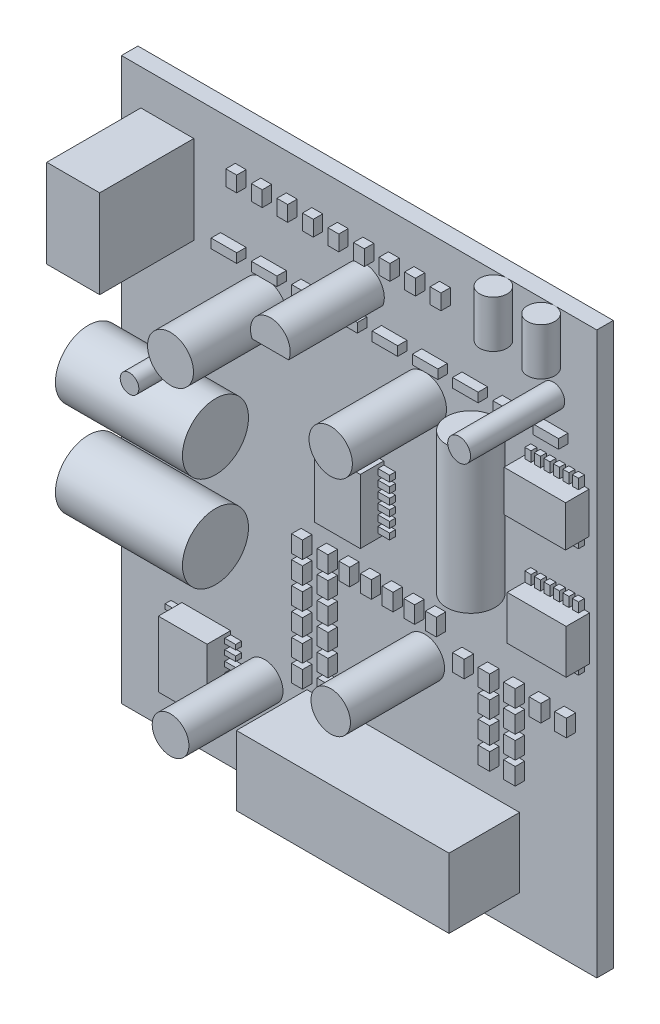
SolidWorks part; units mm, degrees
ref_plane "Plan de face" through (0, 0, 0) normal (0, 0, 1) x (1, 0, 0)
ref_plane "Plan de dessus" through (0, 0, 0) normal (0, 1, 0) x (1, 0, 0)
ref_plane "Plan de droite" through (0, 0, 0) normal (1, 0, 0) x (0, 0, -1)
sketch "Esquisse1" plane through (0, 0, 0) normal (0, 0, 1) x (1, 0, 0)
  line L1 (0, 0) -> (40.4, 0)
  line L2 (0, 0) -> (0, 47.7)
  line L3 (0, 47.7) -> (40.4, 47.7)
  line L4 (40.4, 0) -> (40.4, 47.7)
  dimension "D1" = 40.4
  dimension "D2" = 47.7
extrude "Extrusion1" add sketch "Esquisse1" along normal blind 1.4
sketch "Esquisse2" plane through (0, 0, 1.4) normal (0, 0, 1) x (1, 0, 0)
  line L1 (1.6498, 44.6665) -> (6.1498, 44.6665)
  line L2 (1.6498, 44.6665) -> (1.6498, 37.1665)
  line L3 (1.6498, 37.1665) -> (6.1498, 37.1665)
  line L4 (6.1498, 44.6665) -> (6.1498, 37.1665)
  dimension "D1" = 7.5
  dimension "D2" = 4.5
extrude "Extrusion2" add sketch "Esquisse2" along normal blind 8
sketch "Esquisse3" plane through (0, 0, 1.4) normal (0, 0, 1) x (1, 0, 0)
  line L0 (19.0987, 40.3981) -> (22.2105, 40.3981)
  circle A0 centre (8.6862, 31.9057) radius 0.7919
  circle A1 centre (12.1715, 35.4567) radius 1.9519
  circle A2 centre (25.7839, 35.4567) radius 1.8425
  arc A3 (22.2105, 40.3981) -> (19.0987, 40.3981) centre (20.6546, 41.0464) ccw
  circle A4 centre (12.1715, 7.7708) radius 1.559
  circle A5 centre (25.7839, 16.3204) radius 1.6766
  circle A6 centre (36.7002, 41.0464) radius 0.9709
extrude "Extrusion3" add sketch "Esquisse3" along normal blind 8
sketch "Esquisse4" plane through (0, 0, 1.4) normal (0, 0, 1) x (1, 0, 0)
  line L1 (15.7714, 8.9071) -> (33.8392, 8.9071)
  line L2 (15.7714, 8.9071) -> (15.7714, 2.9981)
  line L3 (15.7714, 2.9981) -> (33.8392, 2.9981)
  line L4 (33.8392, 8.9071) -> (33.8392, 2.9981)
extrude "Extrusion4" add sketch "Esquisse4" along normal blind 6
ref_plane "Plan1" through (0, 25, 0) normal (0, 1, 0) x (-1, 0, 0)
sketch "Esquisse5" plane through (0, 25, 0) normal (0, 1, 0) x (-1, 0, 0)
  line L0 (-40.4, 1.4) -> (0, 1.4) construction
  circle A0 centre (-31.7474, 3.4583) radius 2.0583
extrude "Extrusion5" add sketch "Esquisse5" along normal blind 12
sketch "Esquisse6" plane through (0, 0, 1.4) normal (0, 0, 1) x (1, 0, 0)
  line L1 (34.5087, 35.654) -> (39.7463, 35.654)
  line L2 (34.5087, 35.654) -> (34.5087, 32.1687)
  line L3 (34.5087, 32.1687) -> (39.7463, 32.1687)
  line L4 (39.7463, 35.654) -> (39.7463, 32.1687)
  line L5 (34.7835, 26.5791) -> (39.7973, 26.5791)
  line L6 (34.7835, 26.5791) -> (34.7835, 22.8307)
  line L7 (34.7835, 22.8307) -> (39.7973, 22.8307)
  line L8 (39.7973, 26.5791) -> (39.7973, 22.8307)
  line L9 (18.4188, 29.0122) -> (22.2986, 29.0122)
  line L10 (18.4188, 29.0122) -> (18.4188, 23.5541)
  line L11 (18.4188, 23.5541) -> (22.2986, 23.5541)
  line L12 (22.2986, 29.0122) -> (22.2986, 23.5541)
  line L13 (5.1351, 10.0074) -> (9.2781, 10.0074)
  line L14 (5.1351, 10.0074) -> (5.1351, 4.4178)
  line L15 (5.1351, 4.4178) -> (9.2781, 4.4178)
  line L16 (9.2781, 10.0074) -> (9.2781, 4.4178)
extrude "Extrusion6" add sketch "Esquisse6" along normal blind 2
sketch "Esquisse7" plane through (0, 0, 1.4) normal (0, 0, 1) x (1, 0, 0)
  line L1 (34.7835, 35.654) -> (35.3096, 35.654)
  line L2 (34.7835, 35.654) -> (34.7835, 36.5089)
  line L3 (34.7835, 36.5089) -> (35.3096, 36.5089)
  line L4 (35.3096, 35.654) -> (35.3096, 36.5089)
  line L5 (35.5906, 35.654) -> (35.5906, 36.5089)
  line L6 (35.5906, 35.654) -> (36.1167, 35.654)
  line L7 (35.5906, 36.5089) -> (36.1167, 36.5089)
  line L8 (36.1167, 35.654) -> (36.1167, 36.5089)
  line L9 (36.3977, 35.654) -> (36.3977, 36.5089)
  line L10 (36.3977, 35.654) -> (36.9237, 35.654)
  line L11 (36.3977, 36.5089) -> (36.9237, 36.5089)
  line L12 (36.9237, 35.654) -> (36.9237, 36.5089)
  line L13 (37.2047, 35.654) -> (37.2047, 36.5089)
  line L14 (37.2047, 35.654) -> (37.7308, 35.654)
  line L15 (37.2047, 36.5089) -> (37.7308, 36.5089)
  line L16 (37.7308, 35.654) -> (37.7308, 36.5089)
  line L17 (38.0118, 35.654) -> (38.0118, 36.5089)
  line L18 (38.0118, 35.654) -> (38.5379, 35.654)
  line L19 (38.0118, 36.5089) -> (38.5379, 36.5089)
  line L20 (38.5379, 35.654) -> (38.5379, 36.5089)
  line L21 (38.8189, 35.654) -> (38.8189, 36.5089)
  line L22 (38.8189, 35.654) -> (39.345, 35.654)
  line L23 (38.8189, 36.5089) -> (39.345, 36.5089)
  line L24 (39.345, 35.654) -> (39.345, 36.5089)
  line L25 (39.7463, 33.9114) -> (36.0147, 33.9114) construction
  line L26 (39.7463, 32.1687) -> (39.7463, 35.654) construction
  line L27 (39.345, 32.1687) -> (39.345, 31.3138)
  line L28 (38.8189, 31.3138) -> (39.345, 31.3138)
  line L29 (38.8189, 32.1687) -> (39.345, 32.1687)
  line L30 (38.8189, 32.1687) -> (38.8189, 31.3138)
  line L31 (38.5379, 32.1687) -> (38.5379, 31.3138)
  line L32 (38.0118, 31.3138) -> (38.5379, 31.3138)
  line L33 (38.0118, 32.1687) -> (38.5379, 32.1687)
  line L34 (38.0118, 32.1687) -> (38.0118, 31.3138)
  line L35 (37.7308, 32.1687) -> (37.7308, 31.3138)
  line L36 (37.2047, 31.3138) -> (37.7308, 31.3138)
  line L37 (37.2047, 32.1687) -> (37.7308, 32.1687)
  line L38 (37.2047, 32.1687) -> (37.2047, 31.3138)
  line L39 (36.9237, 32.1687) -> (36.9237, 31.3138)
  line L40 (36.3977, 31.3138) -> (36.9237, 31.3138)
  line L41 (36.3977, 32.1687) -> (36.9237, 32.1687)
  line L42 (36.3977, 32.1687) -> (36.3977, 31.3138)
  line L43 (36.1167, 32.1687) -> (36.1167, 31.3138)
  line L44 (35.5906, 31.3138) -> (36.1167, 31.3138)
  line L45 (35.5906, 32.1687) -> (36.1167, 32.1687)
  line L46 (35.5906, 32.1687) -> (35.5906, 31.3138)
  line L47 (35.3096, 32.1687) -> (35.3096, 31.3138)
  line L48 (34.7835, 31.3138) -> (35.3096, 31.3138)
  line L49 (34.7835, 32.1687) -> (34.7835, 31.3138)
  line L50 (34.7835, 32.1687) -> (35.3096, 32.1687)
  line L52 (34.7835, 26.5791) -> (35.3096, 26.5791)
  line L53 (34.7835, 26.5791) -> (34.7835, 27.4044)
  line L54 (34.7835, 27.4044) -> (35.3096, 27.4044)
  line L55 (35.3096, 26.5791) -> (35.3096, 27.4044)
  line L56 (35.5906, 26.5791) -> (35.5906, 27.4044)
  line L57 (35.5906, 27.4044) -> (36.1167, 27.4044)
  line L58 (36.1167, 26.5791) -> (36.1167, 27.4044)
  line L59 (35.5906, 26.5791) -> (36.1167, 26.5791)
  line L60 (36.3977, 26.5791) -> (36.3977, 27.4044)
  line L61 (36.3977, 27.4044) -> (36.9237, 27.4044)
  line L62 (36.9237, 26.5791) -> (36.9237, 27.4044)
  line L63 (36.3977, 26.5791) -> (36.9237, 26.5791)
  line L64 (37.2047, 26.5791) -> (37.2047, 27.4044)
  line L65 (37.2047, 27.4044) -> (37.7308, 27.4044)
  line L66 (37.7308, 26.5791) -> (37.7308, 27.4044)
  line L67 (37.2047, 26.5791) -> (37.7308, 26.5791)
  line L68 (38.0118, 26.5791) -> (38.0118, 27.4044)
  line L69 (38.0118, 27.4044) -> (38.5379, 27.4044)
  line L70 (38.5379, 26.5791) -> (38.5379, 27.4044)
  line L71 (38.0118, 26.5791) -> (38.5379, 26.5791)
  line L72 (38.8189, 26.5791) -> (38.8189, 27.4044)
  line L73 (38.8189, 27.4044) -> (39.345, 27.4044)
  line L74 (39.345, 26.5791) -> (39.345, 27.4044)
  line L75 (38.8189, 26.5791) -> (39.345, 26.5791)
  line L76 (39.7973, 24.7049) -> (35.7927, 24.7049) construction
  line L77 (39.7973, 22.8307) -> (39.7973, 26.5791) construction
  line L78 (38.8189, 22.8307) -> (39.345, 22.8307)
  line L79 (39.345, 22.8307) -> (39.345, 22.0054)
  line L80 (38.8189, 22.0054) -> (39.345, 22.0054)
  line L81 (38.8189, 22.8307) -> (38.8189, 22.0054)
  line L82 (38.0118, 22.8307) -> (38.5379, 22.8307)
  line L83 (38.5379, 22.8307) -> (38.5379, 22.0054)
  line L84 (38.0118, 22.0054) -> (38.5379, 22.0054)
  line L85 (38.0118, 22.8307) -> (38.0118, 22.0054)
  line L86 (37.2047, 22.8307) -> (37.7308, 22.8307)
  line L87 (37.7308, 22.8307) -> (37.7308, 22.0054)
  line L88 (37.2047, 22.0054) -> (37.7308, 22.0054)
  line L89 (37.2047, 22.8307) -> (37.2047, 22.0054)
  line L90 (36.3977, 22.8307) -> (36.9237, 22.8307)
  line L91 (36.9237, 22.8307) -> (36.9237, 22.0054)
  line L92 (36.3977, 22.0054) -> (36.9237, 22.0054)
  line L93 (36.3977, 22.8307) -> (36.3977, 22.0054)
  line L94 (35.5906, 22.8307) -> (36.1167, 22.8307)
  line L95 (36.1167, 22.8307) -> (36.1167, 22.0054)
  line L96 (35.5906, 22.0054) -> (36.1167, 22.0054)
  line L97 (35.5906, 22.8307) -> (35.5906, 22.0054)
  line L98 (35.3096, 22.8307) -> (35.3096, 22.0054)
  line L99 (34.7835, 22.0054) -> (35.3096, 22.0054)
  line L100 (34.7835, 22.8307) -> (34.7835, 22.0054)
  line L101 (34.7835, 22.8307) -> (35.3096, 22.8307)
  line L102 (22.2986, 23.5541) -> (22.2986, 29.0122) construction
  line L103 (22.2986, 28.6995) -> (23.2857, 28.6995)
  line L104 (22.2986, 28.6995) -> (22.2986, 28.1814)
  line L105 (22.2986, 28.1814) -> (23.2857, 28.1814)
  line L106 (23.2857, 28.6995) -> (23.2857, 28.1814)
  line L107 (22.2986, 27.3304) -> (23.2857, 27.3304)
  line L108 (22.2986, 27.8484) -> (22.2986, 27.3304)
  line L109 (22.2986, 27.8484) -> (23.2857, 27.8484)
  line L110 (23.2857, 27.8484) -> (23.2857, 27.3304)
  line L111 (22.2986, 26.4793) -> (23.2857, 26.4793)
  line L112 (22.2986, 26.9974) -> (22.2986, 26.4793)
  line L113 (22.2986, 26.9974) -> (23.2857, 26.9974)
  line L114 (23.2857, 26.9974) -> (23.2857, 26.4793)
  line L115 (22.2986, 25.6282) -> (23.2857, 25.6282)
  line L116 (22.2986, 26.1463) -> (22.2986, 25.6282)
  line L117 (22.2986, 26.1463) -> (23.2857, 26.1463)
  line L118 (23.2857, 26.1463) -> (23.2857, 25.6282)
  line L119 (22.2986, 24.7772) -> (23.2857, 24.7772)
  line L120 (22.2986, 25.2952) -> (22.2986, 24.7772)
  line L121 (22.2986, 25.2952) -> (23.2857, 25.2952)
  line L122 (23.2857, 25.2952) -> (23.2857, 24.7772)
  line L123 (22.2986, 23.9261) -> (23.2857, 23.9261)
  line L124 (22.2986, 24.4441) -> (22.2986, 23.9261)
  line L125 (22.2986, 24.4441) -> (23.2857, 24.4441)
  line L126 (23.2857, 24.4441) -> (23.2857, 23.9261)
  line L127 (20.3587, 29.0122) -> (20.3587, 22.2707) construction
  line L128 (22.2986, 29.0122) -> (18.4188, 29.0122) construction
  line L129 (17.4318, 24.4441) -> (17.4318, 23.9261)
  line L130 (18.4188, 24.4441) -> (17.4318, 24.4441)
  line L131 (18.4188, 24.4441) -> (18.4188, 23.9261)
  line L132 (18.4188, 23.9261) -> (17.4318, 23.9261)
  line L133 (17.4318, 25.2952) -> (17.4318, 24.7772)
  line L134 (18.4188, 25.2952) -> (17.4318, 25.2952)
  line L135 (18.4188, 25.2952) -> (18.4188, 24.7772)
  line L136 (18.4188, 24.7772) -> (17.4318, 24.7772)
  line L137 (17.4318, 26.1463) -> (17.4318, 25.6282)
  line L138 (18.4188, 26.1463) -> (17.4318, 26.1463)
  line L139 (18.4188, 26.1463) -> (18.4188, 25.6282)
  line L140 (18.4188, 25.6282) -> (17.4318, 25.6282)
  line L141 (17.4318, 26.9974) -> (17.4318, 26.4793)
  line L142 (18.4188, 26.9974) -> (17.4318, 26.9974)
  line L143 (18.4188, 26.9974) -> (18.4188, 26.4793)
  line L144 (18.4188, 26.4793) -> (17.4318, 26.4793)
  line L145 (17.4318, 27.8484) -> (17.4318, 27.3304)
  line L146 (18.4188, 27.8484) -> (17.4318, 27.8484)
  line L147 (18.4188, 27.8484) -> (18.4188, 27.3304)
  line L148 (18.4188, 27.3304) -> (17.4318, 27.3304)
  line L149 (17.4318, 28.6995) -> (17.4318, 28.1814)
  line L150 (18.4188, 28.1814) -> (17.4318, 28.1814)
  line L151 (18.4188, 28.6995) -> (18.4188, 28.1814)
  line L152 (18.4188, 28.6995) -> (17.4318, 28.6995)
  line L153 (9.2781, 4.4178) -> (9.2781, 10.0074) construction
  line L154 (9.2781, 9.7011) -> (10.2039, 9.7011)
  line L155 (9.2781, 9.7011) -> (9.2781, 9.2913)
  line L156 (9.2781, 9.2913) -> (10.2039, 9.2913)
  line L157 (10.2039, 9.7011) -> (10.2039, 9.2913)
  line L158 (9.2781, 8.8523) -> (10.2039, 8.8523)
  line L159 (9.2781, 8.8523) -> (9.2781, 8.4425)
  line L160 (9.2781, 8.4425) -> (10.2039, 8.4425)
  line L161 (10.2039, 8.8523) -> (10.2039, 8.4425)
  line L162 (9.2781, 8.0034) -> (10.2039, 8.0034)
  line L163 (9.2781, 8.0034) -> (9.2781, 7.5936)
  line L164 (9.2781, 7.5936) -> (10.2039, 7.5936)
  line L165 (10.2039, 8.0034) -> (10.2039, 7.5936)
  line L166 (9.2781, 7.1546) -> (10.2039, 7.1546)
  line L167 (9.2781, 7.1546) -> (9.2781, 6.7448)
  line L168 (9.2781, 6.7448) -> (10.2039, 6.7448)
  line L169 (10.2039, 7.1546) -> (10.2039, 6.7448)
  line L170 (9.2781, 6.3057) -> (10.2039, 6.3057)
  line L171 (9.2781, 6.3057) -> (9.2781, 5.896)
  line L172 (9.2781, 5.896) -> (10.2039, 5.896)
  line L173 (10.2039, 6.3057) -> (10.2039, 5.896)
  line L174 (9.2781, 5.4569) -> (10.2039, 5.4569)
  line L175 (9.2781, 5.4569) -> (9.2781, 5.0471)
  line L176 (9.2781, 5.0471) -> (10.2039, 5.0471)
  line L177 (10.2039, 5.4569) -> (10.2039, 5.0471)
  line L178 (7.2066, 10.0074) -> (7.2066, 2.9982) construction
  line L179 (9.2781, 10.0074) -> (5.1351, 10.0074) construction
  line L180 (4.2093, 5.4569) -> (4.2093, 5.0471)
  line L181 (5.1351, 5.0471) -> (4.2093, 5.0471)
  line L182 (5.1351, 5.4569) -> (5.1351, 5.0471)
  line L183 (5.1351, 5.4569) -> (4.2093, 5.4569)
  line L184 (4.2093, 6.3057) -> (4.2093, 5.896)
  line L185 (5.1351, 5.896) -> (4.2093, 5.896)
  line L186 (5.1351, 6.3057) -> (5.1351, 5.896)
  line L187 (5.1351, 6.3057) -> (4.2093, 6.3057)
  line L188 (4.2093, 7.1546) -> (4.2093, 6.7448)
  line L189 (5.1351, 6.7448) -> (4.2093, 6.7448)
  line L190 (5.1351, 7.1546) -> (5.1351, 6.7448)
  line L191 (5.1351, 7.1546) -> (4.2093, 7.1546)
  line L192 (4.2093, 8.0034) -> (4.2093, 7.5936)
  line L193 (5.1351, 7.5936) -> (4.2093, 7.5936)
  line L194 (5.1351, 8.0034) -> (5.1351, 7.5936)
  line L195 (5.1351, 8.0034) -> (4.2093, 8.0034)
  line L196 (4.2093, 8.8523) -> (4.2093, 8.4425)
  line L197 (5.1351, 8.4425) -> (4.2093, 8.4425)
  line L198 (5.1351, 8.8523) -> (5.1351, 8.4425)
  line L199 (5.1351, 8.8523) -> (4.2093, 8.8523)
  line L200 (4.2093, 9.7011) -> (4.2093, 9.2913)
  line L201 (5.1351, 9.2913) -> (4.2093, 9.2913)
  line L202 (5.1351, 9.7011) -> (5.1351, 9.2913)
  line L203 (5.1351, 9.7011) -> (4.2093, 9.7011)
extrude "Extrusion7" add sketch "Esquisse7" along normal blind 0.5
sketch "Esquisse8" plane through (0, 0, 1.4) normal (0, 0, 1) x (1, 0, 0)
  line L0 (11.8427, 44.5974) -> (12.7634, 44.5974)
  line L1 (9.6726, 44.5974) -> (10.5933, 44.5974)
  line L2 (9.6726, 44.5974) -> (9.6726, 43.2822)
  line L3 (9.6726, 43.2822) -> (10.5933, 43.2822)
  line L4 (10.5933, 44.5974) -> (10.5933, 43.2822)
  line L5 (11.8427, 44.5974) -> (11.8427, 43.2822)
  line L6 (11.8427, 43.2822) -> (12.7634, 43.2822)
  line L7 (12.7634, 44.5974) -> (12.7634, 43.2822)
  line L8 (14.0128, 44.5974) -> (14.9335, 44.5974)
  line L9 (14.0128, 44.5974) -> (14.0128, 43.2822)
  line L10 (14.0128, 43.2822) -> (14.9335, 43.2822)
  line L11 (14.9335, 44.5974) -> (14.9335, 43.2822)
  line L12 (16.1829, 44.5974) -> (17.1036, 44.5974)
  line L13 (16.1829, 44.5974) -> (16.1829, 43.2822)
  line L14 (16.1829, 43.2822) -> (17.1036, 43.2822)
  line L15 (17.1036, 44.5974) -> (17.1036, 43.2822)
  line L16 (18.353, 44.5974) -> (19.2737, 44.5974)
  line L17 (18.353, 44.5974) -> (18.353, 43.2822)
  line L18 (18.353, 43.2822) -> (19.2737, 43.2822)
  line L19 (19.2737, 44.5974) -> (19.2737, 43.2822)
  line L20 (20.5231, 44.5974) -> (21.4438, 44.5974)
  line L21 (20.5231, 44.5974) -> (20.5231, 43.2822)
  line L22 (20.5231, 43.2822) -> (21.4438, 43.2822)
  line L23 (21.4438, 44.5974) -> (21.4438, 43.2822)
  line L24 (22.6932, 44.5974) -> (23.6139, 44.5974)
  line L25 (22.6932, 44.5974) -> (22.6932, 43.2822)
  line L26 (22.6932, 43.2822) -> (23.6139, 43.2822)
  line L27 (23.6139, 44.5974) -> (23.6139, 43.2822)
  line L28 (24.8633, 44.5974) -> (25.7839, 44.5974)
  line L29 (24.8633, 44.5974) -> (24.8633, 43.2822)
  line L30 (24.8633, 43.2822) -> (25.7839, 43.2822)
  line L31 (25.7839, 44.5974) -> (25.7839, 43.2822)
  line L32 (27.0334, 44.5974) -> (27.954, 44.5974)
  line L33 (27.0334, 44.5974) -> (27.0334, 43.2822)
  line L34 (27.0334, 43.2822) -> (27.954, 43.2822)
  line L35 (27.954, 44.5974) -> (27.954, 43.2822)
  line L36 (11.8427, 38.0872) -> (14.0128, 38.0872)
  line L37 (8.4232, 38.8763) -> (10.5933, 38.8763)
  line L38 (8.4232, 38.8763) -> (8.4232, 38.0872)
  line L39 (8.4232, 38.0872) -> (10.5933, 38.0872)
  line L40 (10.5933, 38.8763) -> (10.5933, 38.0872)
  line L41 (11.8427, 38.8763) -> (11.8427, 38.0872)
  line L42 (11.8427, 38.8763) -> (14.0128, 38.8763)
  line L43 (14.0128, 38.8763) -> (14.0128, 38.0872)
  line L44 (15.2623, 38.0872) -> (17.4324, 38.0872)
  line L45 (15.2623, 38.8763) -> (15.2623, 38.0872)
  line L46 (15.2623, 38.8763) -> (17.4324, 38.8763)
  line L47 (17.4324, 38.8763) -> (17.4324, 38.0872)
  line L48 (18.6818, 38.0872) -> (20.8519, 38.0872)
  line L49 (18.6818, 38.8763) -> (18.6818, 38.0872)
  line L50 (18.6818, 38.8763) -> (20.8519, 38.8763)
  line L51 (20.8519, 38.8763) -> (20.8519, 38.0872)
  line L52 (22.1014, 38.0872) -> (24.2715, 38.0872)
  line L53 (22.1014, 38.8763) -> (22.1014, 38.0872)
  line L54 (22.1014, 38.8763) -> (24.2715, 38.8763)
  line L55 (24.2715, 38.8763) -> (24.2715, 38.0872)
  line L56 (25.5209, 38.0872) -> (27.691, 38.0872)
  line L57 (25.5209, 38.8763) -> (25.5209, 38.0872)
  line L58 (25.5209, 38.8763) -> (27.691, 38.8763)
  line L59 (27.691, 38.8763) -> (27.691, 38.0872)
  line L60 (28.9405, 38.0872) -> (31.1106, 38.0872)
  line L61 (28.9405, 38.8763) -> (28.9405, 38.0872)
  line L62 (28.9405, 38.8763) -> (31.1106, 38.8763)
  line L63 (31.1106, 38.8763) -> (31.1106, 38.0872)
  line L64 (32.36, 38.0872) -> (34.5301, 38.0872)
  line L65 (32.36, 38.8763) -> (32.36, 38.0872)
  line L66 (32.36, 38.8763) -> (34.5301, 38.8763)
  line L67 (34.5301, 38.8763) -> (34.5301, 38.0872)
  line L68 (35.7795, 38.0872) -> (37.9496, 38.0872)
  line L69 (35.7795, 38.8763) -> (35.7795, 38.0872)
  line L70 (35.7795, 38.8763) -> (37.9496, 38.8763)
  line L71 (37.9496, 38.8763) -> (37.9496, 38.0872)
  line L72 (17.4324, 18.622) -> (18.353, 18.622)
  line L73 (15.2623, 20.5291) -> (16.1829, 20.5291)
  line L74 (15.2623, 20.5291) -> (15.2623, 19.0824)
  line L75 (15.2623, 19.0824) -> (16.1829, 19.0824)
  line L76 (16.1829, 20.5291) -> (16.1829, 19.0824)
  line L77 (17.4324, 20.5291) -> (18.353, 20.5291)
  line L78 (17.4324, 20.5291) -> (17.4324, 19.0824)
  line L79 (17.4324, 19.0824) -> (18.353, 19.0824)
  line L80 (18.353, 20.5291) -> (18.353, 19.0824)
  line L81 (15.2623, 18.622) -> (16.1829, 18.622)
  line L82 (17.4324, 17.1753) -> (18.353, 17.1753)
  line L83 (15.2623, 18.622) -> (15.2623, 17.1753)
  line L84 (17.4324, 18.622) -> (17.4324, 17.1753)
  line L85 (15.2623, 17.1753) -> (16.1829, 17.1753)
  line L86 (16.1829, 18.622) -> (16.1829, 17.1753)
  line L87 (18.353, 18.622) -> (18.353, 17.1753)
  line L88 (17.4324, 16.715) -> (18.353, 16.715)
  line L89 (15.2623, 16.715) -> (16.1829, 16.715)
  line L90 (17.4324, 15.2683) -> (18.353, 15.2683)
  line L91 (15.2623, 16.715) -> (15.2623, 15.2683)
  line L92 (17.4324, 16.715) -> (17.4324, 15.2683)
  line L93 (15.2623, 15.2683) -> (16.1829, 15.2683)
  line L94 (16.1829, 16.715) -> (16.1829, 15.2683)
  line L95 (18.353, 16.715) -> (18.353, 15.2683)
  line L96 (17.4324, 14.8079) -> (18.353, 14.8079)
  line L97 (15.2623, 14.8079) -> (16.1829, 14.8079)
  line L98 (17.4324, 13.3612) -> (18.353, 13.3612)
  line L99 (15.2623, 14.8079) -> (15.2623, 13.3612)
  line L100 (17.4324, 14.8079) -> (17.4324, 13.3612)
  line L101 (15.2623, 13.3612) -> (16.1829, 13.3612)
  line L102 (16.1829, 14.8079) -> (16.1829, 13.3612)
  line L103 (18.353, 14.8079) -> (18.353, 13.3612)
  line L104 (17.4324, 12.9009) -> (18.353, 12.9009)
  line L105 (15.2623, 12.9009) -> (16.1829, 12.9009)
  line L106 (17.4324, 11.4541) -> (18.353, 11.4541)
  line L107 (15.2623, 12.9009) -> (15.2623, 11.4541)
  line L108 (17.4324, 12.9009) -> (17.4324, 11.4541)
  line L109 (15.2623, 11.4541) -> (16.1829, 11.4541)
  line L110 (16.1829, 12.9009) -> (16.1829, 11.4541)
  line L111 (18.353, 12.9009) -> (18.353, 11.4541)
  line L112 (17.4324, 10.9938) -> (18.353, 10.9938)
  line L113 (15.2623, 10.9938) -> (16.1829, 10.9938)
  line L114 (17.4324, 9.5471) -> (18.353, 9.5471)
  line L115 (15.2623, 10.9938) -> (15.2623, 9.5471)
  line L116 (17.4324, 10.9938) -> (17.4324, 9.5471)
  line L117 (15.2623, 9.5471) -> (16.1829, 9.5471)
  line L118 (16.1829, 10.9938) -> (16.1829, 9.5471)
  line L119 (18.353, 10.9938) -> (18.353, 9.5471)
  line L120 (19.2737, 20.5291) -> (20.1943, 20.5291)
  line L121 (20.1943, 20.5291) -> (20.1943, 19.0824)
  line L122 (19.2737, 19.0824) -> (20.1943, 19.0824)
  line L123 (19.2737, 20.5291) -> (19.2737, 19.0824)
  line L124 (21.115, 20.5291) -> (22.0356, 20.5291)
  line L125 (22.0356, 20.5291) -> (22.0356, 19.0824)
  line L126 (21.115, 19.0824) -> (22.0356, 19.0824)
  line L127 (21.115, 20.5291) -> (21.115, 19.0824)
  line L128 (22.9562, 20.5291) -> (23.8769, 20.5291)
  line L129 (23.8769, 20.5291) -> (23.8769, 19.0824)
  line L130 (22.9562, 19.0824) -> (23.8769, 19.0824)
  line L131 (22.9562, 20.5291) -> (22.9562, 19.0824)
  line L132 (24.7975, 20.5291) -> (25.7182, 20.5291)
  line L133 (25.7182, 20.5291) -> (25.7182, 19.0824)
  line L134 (24.7975, 19.0824) -> (25.7182, 19.0824)
  line L135 (24.7975, 20.5291) -> (24.7975, 19.0824)
  line L136 (26.6388, 20.5291) -> (27.5595, 20.5291)
  line L137 (27.5595, 20.5291) -> (27.5595, 19.0824)
  line L138 (26.6388, 19.0824) -> (27.5595, 19.0824)
  line L139 (26.6388, 20.5291) -> (26.6388, 19.0824)
  line L140 (31.1106, 17.1753) -> (32.097, 17.1753)
  line L141 (28.9405, 17.1753) -> (29.9269, 17.1753)
  line L142 (28.9405, 17.1753) -> (28.9405, 18.622)
  line L143 (28.9405, 18.622) -> (29.9269, 18.622)
  line L144 (29.9269, 17.1753) -> (29.9269, 18.622)
  line L145 (32.097, 17.1753) -> (32.097, 18.622)
  line L146 (31.1106, 18.622) -> (32.097, 18.622)
  line L147 (31.1106, 17.1753) -> (31.1106, 18.622)
  line L148 (33.2806, 17.1753) -> (34.2671, 17.1753)
  line L149 (34.2671, 17.1753) -> (34.2671, 18.622)
  line L150 (33.2806, 18.622) -> (34.2671, 18.622)
  line L151 (33.2806, 17.1753) -> (33.2806, 18.622)
  line L152 (35.4507, 17.1753) -> (36.4372, 17.1753)
  line L153 (36.4372, 17.1753) -> (36.4372, 18.622)
  line L154 (35.4507, 18.622) -> (36.4372, 18.622)
  line L155 (35.4507, 17.1753) -> (35.4507, 18.622)
  line L156 (37.6208, 17.1753) -> (38.6073, 17.1753)
  line L157 (38.6073, 17.1753) -> (38.6073, 18.622)
  line L158 (37.6208, 18.622) -> (38.6073, 18.622)
  line L159 (37.6208, 17.1753) -> (37.6208, 18.622)
  line L164 (31.1106, 16.715) -> (32.097, 16.715)
  line L165 (32.097, 15.2683) -> (32.097, 16.715)
  line L166 (31.1106, 15.2683) -> (32.097, 15.2683)
  line L167 (31.1106, 15.2683) -> (31.1106, 16.715)
  line L168 (31.1106, 14.8079) -> (32.097, 14.8079)
  line L169 (32.097, 13.3612) -> (32.097, 14.8079)
  line L170 (31.1106, 13.3612) -> (32.097, 13.3612)
  line L171 (31.1106, 13.3612) -> (31.1106, 14.8079)
  line L172 (31.1106, 12.9009) -> (32.097, 12.9009)
  line L173 (32.097, 11.4541) -> (32.097, 12.9009)
  line L174 (31.1106, 11.4541) -> (32.097, 11.4541)
  line L175 (31.1106, 11.4541) -> (31.1106, 12.9009)
  line L176 (33.2806, 15.2683) -> (33.2806, 16.715)
  line L177 (33.2806, 15.2683) -> (34.2671, 15.2683)
  line L178 (33.2806, 16.715) -> (34.2671, 16.715)
  line L179 (34.2671, 15.2683) -> (34.2671, 16.715)
  line L180 (33.2806, 13.3612) -> (33.2806, 14.8079)
  line L181 (33.2806, 13.3612) -> (34.2671, 13.3612)
  line L182 (33.2806, 14.8079) -> (34.2671, 14.8079)
  line L183 (34.2671, 13.3612) -> (34.2671, 14.8079)
  line L184 (33.2806, 11.4541) -> (33.2806, 12.9009)
  line L185 (33.2806, 11.4541) -> (34.2671, 11.4541)
  line L186 (33.2806, 12.9009) -> (34.2671, 12.9009)
  line L187 (34.2671, 11.4541) -> (34.2671, 12.9009)
extrude "Extrusion8" add sketch "Esquisse8" along normal blind 0.8
sketch "Esquisse9" plane through (0, 0, 0) normal (-1, 0, 0) x (0, 0, 1)
  line L0 (1.4, 47.7) -> (1.4, 0) construction
  circle A0 centre (4.2068, 26.4475) radius 2.8068
  circle A1 centre (4.2068, 18.359) radius 2.8068
extrude "Extrusion9" add sketch "Esquisse9" against normal blind 10.8
sketch "Esquisse10" plane through (0, 47.7, 0) normal (0, 1, 0) x (-1, 0, 0)
  line L0 (-40.4, 1.4) -> (0, 1.4) construction
  circle A0 centre (-36.8276, 2.5612) radius 1.1612
  circle A1 centre (-32.7743, 2.5612) radius 1.1612
extrude "Extrusion10" add sketch "Esquisse10" against normal blind 4
